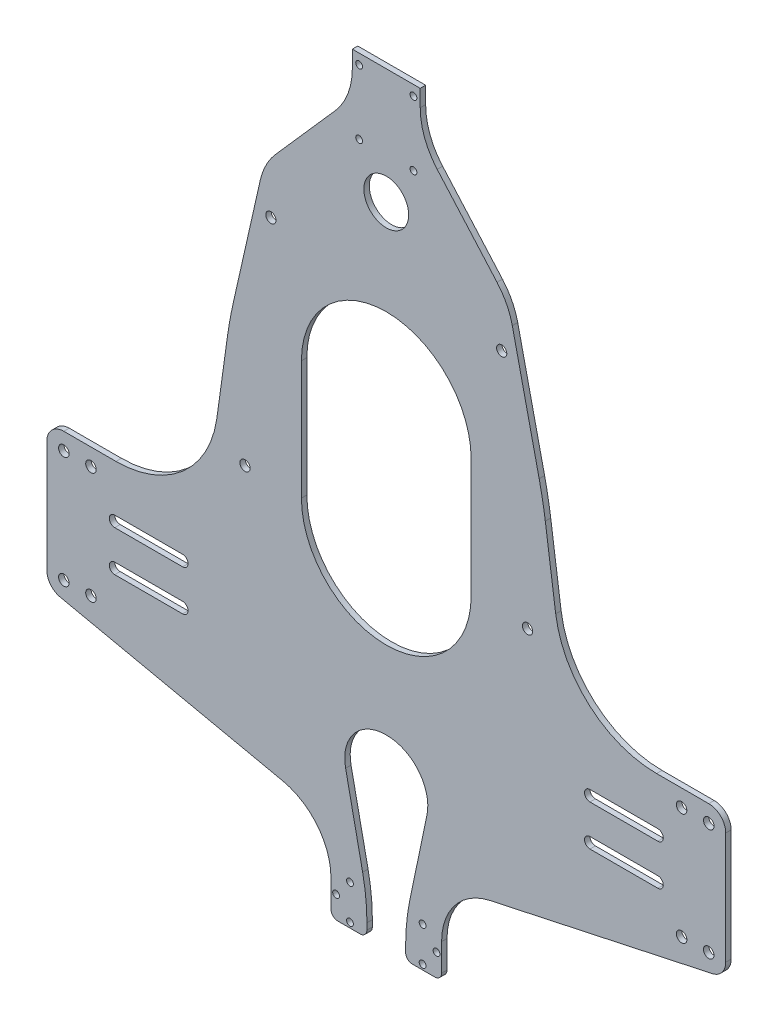
SolidWorks part; units mm, degrees
ref_plane "前视基准面" through (0, 0, 0) normal (0, 0, 1) x (1, 0, 0)
ref_plane "上视基准面" through (0, 0, 0) normal (0, 1, 0) x (1, 0, 0)
ref_plane "右视基准面" through (0, 0, 0) normal (1, 0, 0) x (0, 0, -1)
sketch "草图1" plane through (0, 0, 0) normal (0, 0, 1) x (1, 0, 0)
  line L0 (36, 0) -> (36, -49.0436) construction
  line L1 (0, 0) -> (72, 0) construction
  line L2 (0, 0) -> (0, -40) construction
  line L3 (0, -40) -> (72, -40) construction
  line L4 (72, 0) -> (72, -40) construction
  line L5 (30.3, -128) -> (30.3, -182.6) construction
  line L6 (-10.15, -45) -> (82.15, -45) construction
  line L7 (-10.15, -45) -> (-10.15, -93) construction
  line L8 (-10.15, -93) -> (82.15, -93) construction
  line L9 (82.15, -45) -> (82.15, -93) construction
  line L10 (-13.95, -168) -> (85.95, -168) construction
  line L11 (-13.95, -168) -> (-13.95, -191.7) construction
  line L12 (-13.95, -191.7) -> (85.95, -191.7) construction
  line L13 (85.95, -168) -> (85.95, -191.7) construction
  line L14 (-17.5, -98) -> (89.5, -98) construction
  line L15 (-17.5, -98) -> (-17.5, -128) construction
  line L16 (-17.5, -128) -> (89.5, -128) construction
  line L17 (89.5, -98) -> (89.5, -128) construction
  line L18 (28.3, -182.6) -> (21.7, -182.6)
  line L19 (-64, -103) -> (-64, -135.961)
  line L20 (-59, -98) -> (-43.6267, -98)
  line L21 (-13.9111, -72.1209) -> (-10.8431, -49.9977)
  line L22 (-9.0398, -40.0781) -> (-1.125, -4.9877)
  line L24 (19.7, -172.5406) -> (19.7, -180.6)
  line L25 (30.3, -128) -> (41.7, -128) construction
  line L26 (-60.0512, -140.8492) -> (5.4844, -154.9429)
  line L27 (41.7, -128) -> (41.7, -182.6) construction
  line L28 (43.7, -182.6) -> (50.3, -182.6)
  line L29 (52.3, -172.5406) -> (52.3, -180.6)
  line L30 (132.0512, -140.8492) -> (66.5156, -154.9429)
  line L31 (136, -103) -> (136, -135.961)
  line L32 (131, -98) -> (115.6267, -98)
  line L33 (85.9111, -72.1209) -> (82.8431, -49.9977)
  line L34 (81.0398, -40.0781) -> (73.125, -4.9877)
  line L36 (30.3, -180.6) -> (30.3, -178.7377)
  line L37 (29.0334, -166.4743) -> (24.0177, -142.4527)
  line L38 (35.7644, -128) -> (36.2356, -128)
  line L39 (41.7, -180.6) -> (41.7, -178.7377)
  line L40 (42.9666, -166.4743) -> (47.9823, -142.4527)
  line L41 (36, -80.046) -> (36, -45) construction
  line L42 (11, -80.046) -> (11, -45)
  line L43 (61, -80.046) -> (61, -45)
  line L44 (5.8269, 29.5) -> (62.1731, 29.5) construction
  line L45 (3.3807, 3.8358) -> (21.0042, 23.8317)
  line L46 (26, 37.0557) -> (26, 42)
  line L47 (26, 42) -> (46, 42)
  line L48 (68.6193, 3.8358) -> (50.9958, 23.8317)
  line L49 (46, 37.0557) -> (46, 42)
  line L50 (-55, -93.8291) -> (-55, -150.8088) construction
  line L51 (-44, -113.4805) -> (-24, -113.4805) construction
  line L54 (-44, -111.8805) -> (-24, -111.8805)
  line L55 (-44, -115.0805) -> (-24, -115.0805)
  line L56 (-44, -125.4805) -> (-24, -125.4805) construction
  line L59 (-64, -119.4805) -> (136, -119.4805) construction
  line L60 (-44, -127.0805) -> (-24, -127.0805)
  line L61 (-44, -123.8805) -> (-24, -123.8805)
  line L62 (116, -113.4805) -> (96, -113.4805) construction
  line L63 (116, -111.8805) -> (96, -111.8805)
  line L64 (116, -115.0805) -> (96, -115.0805)
  line L65 (116, -125.4805) -> (96, -125.4805) construction
  line L66 (116, -127.0805) -> (96, -127.0805)
  line L67 (116, -123.8805) -> (96, -123.8805)
  circle A0 centre (2, -12.95) radius 1.5
  circle A1 centre (70, -12.95) radius 1.5
  circle A2 centre (-5.6215, -80.046) radius 1.5
  circle A3 centre (77.6215, -80.046) radius 1.5
  circle A4 centre (25.3, -170.9) radius 1
  circle A5 centre (25.3, -181.1) radius 1
  circle A6 centre (21.2, -176) radius 1
  circle A7 centre (46.7, -181.1) radius 1
  circle A8 centre (50.8, -176) radius 1
  circle A9 centre (46.7, -170.9) radius 1
  arc A10 (52.3, -172.5406) -> (66.5156, -154.9429) centre (70.3, -172.5406) cw
  arc A11 (5.4844, -154.9429) -> (19.7, -172.5406) centre (1.7, -172.5406) cw
  arc A12 (115.6267, -98) -> (85.9111, -72.1209) centre (115.6267, -68) cw
  arc A13 (-43.6267, -98) -> (-13.9111, -72.1209) centre (-43.6267, -68) ccw
  arc A14 (82.8431, -49.9977) -> (81.0398, -40.0781) centre (-36.0194, -66.4815) ccw
  arc A15 (-10.8431, -49.9977) -> (-9.0398, -40.0781) centre (108.0194, -66.4815) cw
  arc A16 (30.3, -178.7377) -> (29.0334, -166.4743) centre (-29.7, -178.7377) ccw
  arc A17 (47.9823, -142.4527) -> (36.2356, -128) centre (36.2356, -140) ccw
  arc A18 (24.0177, -142.4527) -> (35.7644, -128) centre (35.7644, -140) cw
  arc A19 (136, -103) -> (131, -98) centre (131, -103) ccw
  arc A20 (41.7, -178.7377) -> (42.9666, -166.4743) centre (101.7, -178.7377) cw
  arc A21 (132.0512, -140.8492) -> (136, -135.961) centre (131, -135.961) ccw
  arc A22 (-64, -135.961) -> (-60.0512, -140.8492) centre (-59, -135.961) ccw
  arc A23 (-64, -103) -> (-59, -98) centre (-59, -103) cw
  arc A25 (21.7, -182.6) -> (19.7, -180.6) centre (21.7, -180.6) cw
  arc A26 (50.3, -182.6) -> (52.3, -180.6) centre (50.3, -180.6) ccw
  arc A27 (41.7, -180.6) -> (43.7, -182.6) centre (43.7, -180.6) ccw
  arc A28 (30.3, -180.6) -> (28.3, -182.6) centre (28.3, -180.6) cw
  arc A31 (11, -80.046) -> (61, -80.046) centre (36, -80.046) ccw
  arc A32 (61, -45) -> (11, -45) centre (36, -45) ccw
  circle A33 centre (28, 39) radius 1
  circle A34 centre (44, 39) radius 1
  circle A35 centre (44, 20) radius 1
  circle A36 centre (28, 20) radius 1
  circle A37 centre (36, 8) radius 6.6
  circle A38 centre (36, 8) radius 9 construction
  arc A39 (50.9958, 23.8317) -> (46, 37.0557) centre (66, 37.0557) cw
  arc A40 (21.0042, 23.8317) -> (26, 37.0557) centre (6, 37.0557) ccw
  arc A41 (-1.125, -4.9877) -> (3.3807, 3.8358) centre (18.3849, -9.3882) cw
  arc A42 (68.6193, 3.8358) -> (73.125, -4.9877) centre (53.6151, -9.3882) cw
  circle A43 centre (-59, -103) radius 1.55
  circle A44 centre (-59, -135.961) radius 1.55
  circle A45 centre (-51, -135.961) radius 1.55
  circle A46 centre (-51, -103) radius 1.55
  circle A47 centre (131, -135.961) radius 1.55
  circle A48 centre (123, -135.961) radius 1.55
  circle A49 centre (123, -103) radius 1.55
  circle A50 centre (131, -103) radius 1.55
  arc A53 (-44, -111.8805) -> (-44, -115.0805) centre (-44, -113.4805) ccw
  arc A54 (-24, -115.0805) -> (-24, -111.8805) centre (-24, -113.4805) ccw
  arc A57 (-44, -127.0805) -> (-44, -123.8805) centre (-44, -125.4805) cw
  arc A58 (-24, -123.8805) -> (-24, -127.0805) centre (-24, -125.4805) cw
  arc A59 (116, -111.8805) -> (116, -115.0805) centre (116, -113.4805) cw
  arc A60 (96, -115.0805) -> (96, -111.8805) centre (96, -113.4805) cw
  arc A61 (116, -127.0805) -> (116, -123.8805) centre (116, -125.4805) ccw
  arc A62 (96, -123.8805) -> (96, -127.0805) centre (96, -125.4805) ccw
  point P49 (36, -128)
  point P57 (36, -128)
  point P58 (36, -62.523)
  point P63 (52.3, -158)
  point P66 (19.7, -158)
  point P73 (30.3, -172.5406)
  point P85 (51, -128)
  point P88 (21, -128)
  point P93 (136, -98)
  point P96 (136, -140)
  point P99 (-64, -140)
  point P102 (-64, -98)
  point P108 (19.7, -182.6)
  point P111 (52.3, -182.6)
  point P119 (36, 42)
  point P146 (46, 29.5)
  point P149 (26, 29.5)
  point P155 (72, 0)
  point P164 (-34, -113.4805)
  point P171 (-34, -125.4805)
  point P177 (-64, -119.4805)
  point P181 (106, -113.4805)
  point P188 (106, -125.4805)
  dimension "D3" = 3
  dimension "D8" = 3
  dimension "D18" = 2
  dimension "D19" = 2
  dimension "D20" = 2
  dimension "D33" = 18
  dimension "D34" = 30
  dimension "D35" = 120
  dimension "D37" = 60
  dimension "D38" = 12
  dimension "D39" = 5
  dimension "D40" = 18
  dimension "D41" = 3
  dimension "D43" = 2
  dimension "D46" = 13.2
  dimension "D49" = 20
  dimension "D50" = 20
  dimension "D51" = 3.1
  dimension "D52" = 3.1
  dimension "D54" = 1.6
  dimension "D1" = 72
  dimension "D2" = 40
  dimension "D4" = 68
  dimension "D5" = 12.95
  dimension "D6" = 48
  dimension "D7" = 92.3
  dimension "D9" = 83.243
  dimension "D10" = 12.954
  dimension "D11" = 5
  dimension "D12" = 99.9
  dimension "D13" = 23.7
  dimension "D14" = 30
  dimension "D15" = 107
  dimension "D16" = 5
  dimension "D17" = 40
  dimension "D21" = 2.9
  dimension "D22" = 10.7
  dimension "D23" = 4.1
  dimension "D24" = 5.1
  dimension "D25" = 5.1
  dimension "D26" = 200
  dimension "D27" = 12
  dimension "D28" = 1.5
  dimension "D29" = 5
  dimension "D30" = 1.5
  dimension "D31" = 42
  dimension "D32" = 30
  dimension "D36" = 30
  dimension "D42" = 50
  dimension "D44" = 16
  dimension "D45" = 19
  dimension "D47" = 2
  dimension "D48" = 8
  dimension "D53" = 4
  dimension "D56" = 6
  dimension "D57" = 20
  dimension "D58" = 20
extrude "凸台-拉伸1" add sketch "草图1" along normal blind 1.6
